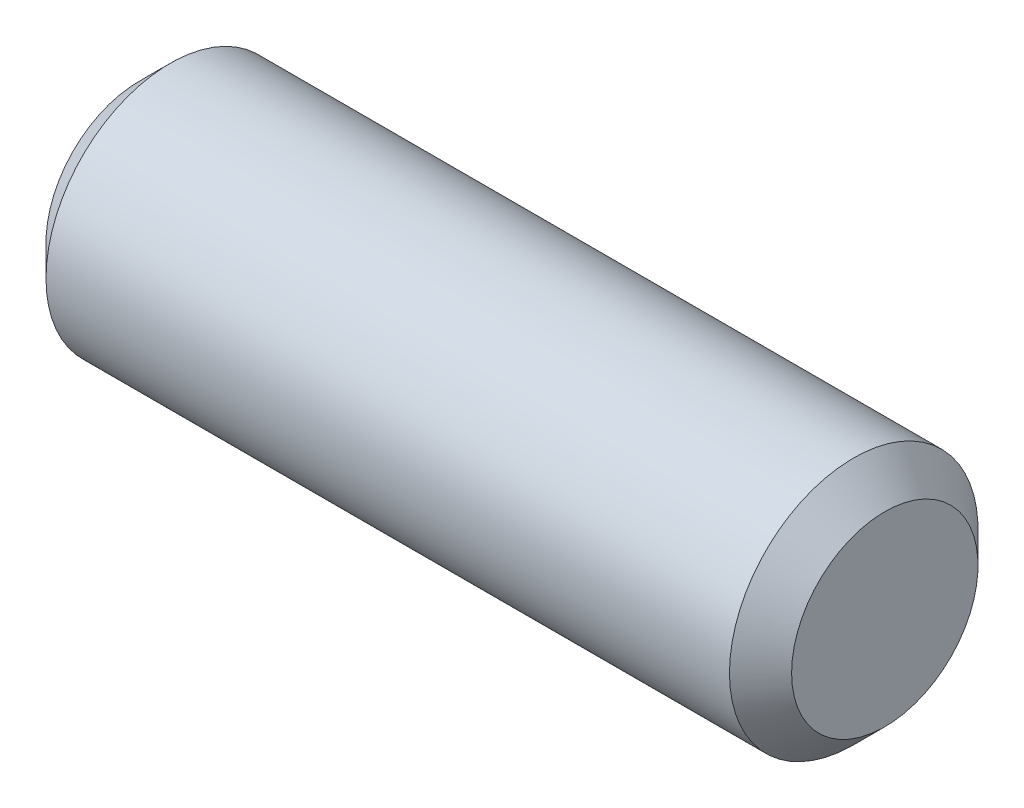
SolidWorks part; units mm, degrees
ref_plane "前基準面" through (0, 0, 0) normal (0, 0, 1) x (1, 0, 0)
ref_plane "上基準面" through (0, 0, 0) normal (0, 1, 0) x (1, 0, 0)
ref_plane "右基準面" through (0, 0, 0) normal (1, 0, 0) x (0, 0, -1)
sketch "草圖1" plane through (0, 0, 0) normal (0, 0, 1) x (1, 0, 0)
  line L1 (0, 0) -> (24, 0)
  line L2 (0, 0) -> (0, 4)
  line L3 (0, 4) -> (24, 4)
  line L4 (24, 0) -> (24, 4)
  dimension "D1" = 4
  dimension "D2" = 24
revolve "旋轉1" add sketch "草圖1" angle 360 about L1
chamfer "導角1" distance 1 angle 45 2 edges at (24, 0, 4) (0, 0, 4)
